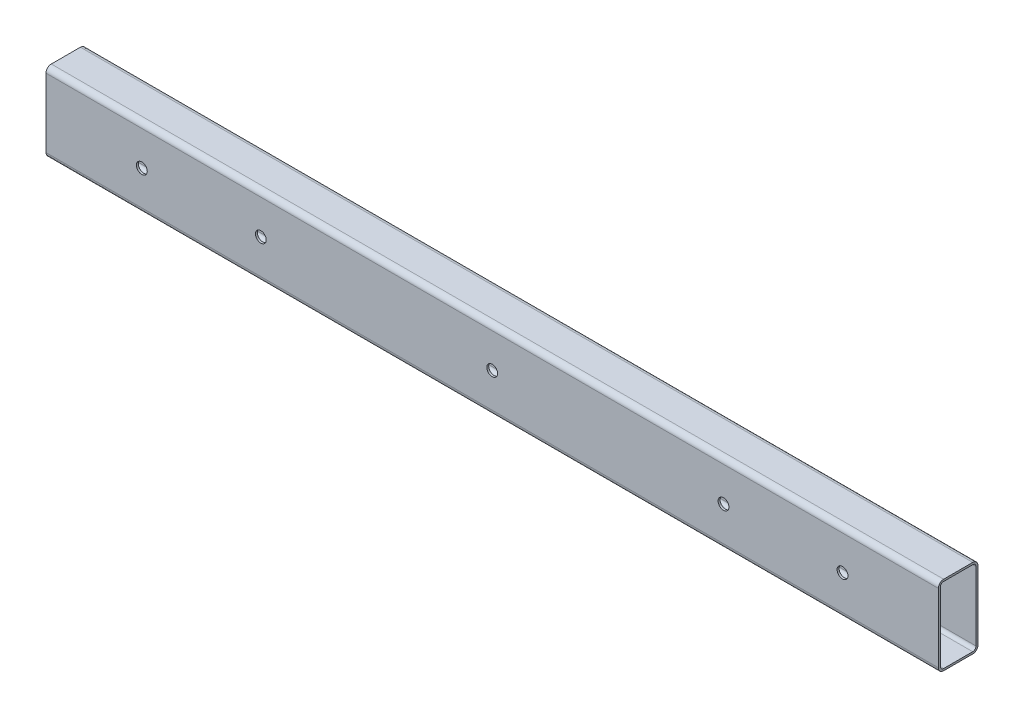
SolidWorks part; units mm, degrees
ref_plane "Front Plane" through (0, 0, 0) normal (0, 0, 1) x (1, 0, 0)
ref_plane "Top Plane" through (0, 0, 0) normal (0, 1, 0) x (1, 0, 0)
ref_plane "Right Plane" through (0, 0, 0) normal (1, 0, 0) x (0, 0, -1)
sketch "Sketch1" plane through (0, 0, 0) normal (1, 0, 0) x (0, 0, -1)
  line L1 (-22, -57) -> (22, -57)
  line L2 (-27, -52) -> (-27, 52)
  line L3 (-22, 57) -> (22, 57)
  line L4 (27, -52) -> (27, 52)
  line L5 (-27, -57) -> (27, 57) construction
  line L6 (-27, 57) -> (27, -57) construction
  arc A0 (-27, -52) -> (-22, -57) centre (-22, -52) ccw
  arc A1 (22, -57) -> (27, -52) centre (22, -52) ccw
  arc A2 (27, 52) -> (22, 57) centre (22, 52) ccw
  arc A3 (-22, 57) -> (-27, 52) centre (-22, 52) ccw
  point P0 (0, 0)
  dimension "D3" = 5
  dimension "D1" = 54
  dimension "D2" = 114
extrude "Extrude-Thin1" add sketch "Sketch1" along normal blind 675 and the other way blind 675 thin
sketch "Sketch2" plane through (0, 0, 0) normal (0, 0, 1) x (1, 0, 0)
  line L0 (0, -25.3) -> (0, 25.3) construction
  circle A0 centre (0, 0) radius 9
  circle A1 centre (-335, 0) radius 9
  circle A2 centre (335, 0) radius 9
  dimension "D1" = 18
  dimension "D2" = 335
extrude "Cut-Extrude1" [suppressed] cut sketch "Sketch2" against normal through all both and the other way through all
sketch "Sketch3" plane through (0, 0, 0) normal (0, 1, 0) x (1, 0, 0)
  line L1 (0, -25.3) -> (0, 25.3) construction
  circle A0 centre (-387.5, 0) radius 5
  circle A1 centre (-312.5, 0) radius 5
  circle A2 centre (312.5, 0) radius 5
  circle A3 centre (387.5, 0) radius 5
  dimension "D1" = 10
  dimension "D2" = 75
  dimension "D3" = 312.5
extrude "Cut-Extrude2" [suppressed] cut sketch "Sketch3" against normal through all both and the other way through all
sketch "Sketch4" plane through (0, 0, 30) normal (0, 0, 1) x (1, 0, 0)
  line L0 (-675, 0) -> (675, 0) construction
  line L1 (-675, 52) -> (-675, -52) construction
  line L2 (675, 52) -> (675, -52) construction
  circle A0 centre (0, 0) radius 8.2
  dimension "D1" = 16.4
extrude "Cut-Extrude3" cut sketch "Sketch4" against normal blind 110 contours A0
extrude "Cut-Extrude4" cut sketch "Sketch5" along normal blind 110
sketch "Sketch5" plane through (0, -1598, -30) normal (0, 0, 1) x (1, 0, 0)
  circle A5 centre (350, 1598) radius 8.2
  circle A6 centre (530, 1598) radius 8.2
  circle A7 centre (0, 1598) radius 8.2
  circle A8 centre (-350, 1598) radius 8.2
  circle A9 centre (-530, 1598) radius 8.2
